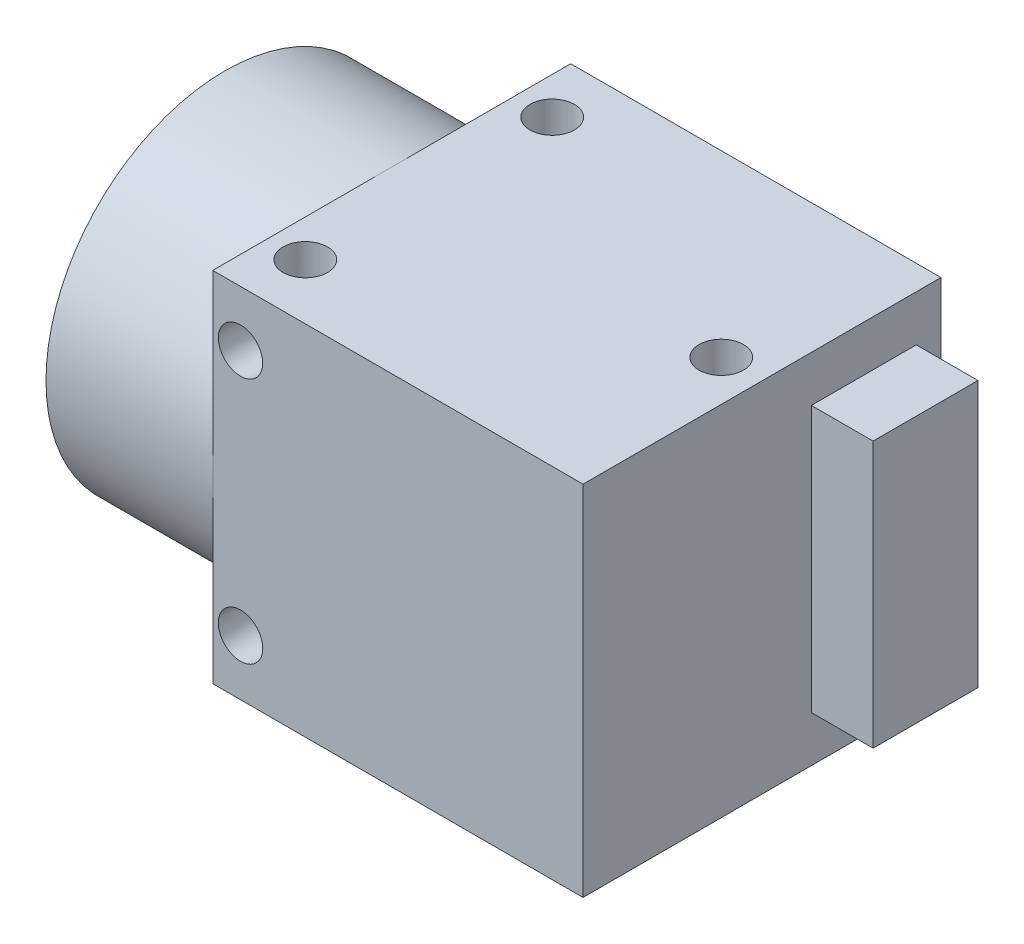
SolidWorks part; units mm, degrees
ref_plane "Front Plane" through (0, 0, 0) normal (0, 0, 1) x (1, 0, 0)
ref_plane "Top Plane" through (0, 0, 0) normal (0, 1, 0) x (1, 0, 0)
ref_plane "Right Plane" through (0, 0, 0) normal (1, 0, 0) x (0, 0, -1)
sketch "Sketch1" plane through (0, 0, 0) normal (1, 0, 0) x (0, -1, 0)
  line L1 (0, 0) -> (29, 0)
  line L2 (0, 0) -> (0, 29)
  line L3 (0, 29) -> (29, 29)
  line L4 (29, 0) -> (29, 29)
  dimension "D1" = 29
extrude "Boss-Extrude1" add sketch "Sketch1" along normal blind 48.51 contours L3 L4 L1 L2
sketch "Sketch2" plane through (0, 0, 0) normal (-1, 0, 0) x (0, 0, 1)
  line L0 (-29, 0) -> (0, -29) construction
  line L1 (0, 0) -> (0, -29) construction
  line L2 (0, -29) -> (-29, -29) construction
  line L3 (0, 0) -> (-29, 0) construction
  line L4 (-29, 0) -> (-29, -29) construction
  line L5 (0, 0) -> (0, -29)
  line L6 (0, -29) -> (-29, -29)
  line L7 (-29, 0) -> (-29, -29)
  line L8 (0, 0) -> (-29, 0)
  circle A0 centre (-14.5, -14.5) radius 14.5
  line M3 (0, 0) -> (-29, 0)
  line M4 (-29, 0) -> (-29, -29)
  line M5 (-29, -29) -> (0, -29)
  line M6 (0, -29) -> (0, 0)
extrude "Cut-Extrude1" cut sketch "Sketch2" against normal blind 13.51 contours L8 L0 A0 | L0 A0 M4 | A0 L7 M5 | L0 A0 L6 | A0 L0 M6 | A0 L5 M3
hole_wizard "M3 Clearance Hole3" positions "Sketch4" profile "Sketch5" hole size "M3" standard "ANSI Metric"
sketch "Sketch4" plane through (0, 0, 0) normal (0, 0, -1) x (1, 0, 0)
  line L0 (15.76, 24.5) -> (15.76, 29) construction
  line L3 (15.76, 4.5) -> (15.76, 0) construction
  line L4 (48.51, 0) -> (13.51, 0) construction
  line L6 (13.51, 14.5) -> (13.51, 0) construction
  line L7 (48.51, 29) -> (13.51, 29) construction
  point P0 (15.76, 24.5)
  point P2 (15.76, 4.5)
  dimension "D1" = 20
  dimension "D2" = 2.25
sketch "Sketch5" plane through (15.76, -24.5, 0) normal (1, 0, 0) x (0, -1, 0)
  line L0 (0, 0) -> (0, 4.0815)
  line L1 (0, 4.0815) -> (1.8, 3)
  line L2 (1.8, 3) -> (1.8, 0)
  line L5 (1.8, 0) -> (0, 0)
  line L10 (0, 4.0815) -> (-1.8, 3) construction
  line L11 (0, -6.35) -> (0, 107.95) construction
  dimension "Hole Dia." = 3.6
  dimension "Hole Depth" = 3
  dimension "Drill Angle" = 118
sketch "Sketch6" plane through (48.51, 0, 0) normal (1, 0, 0) x (0, 0, -1)
  line L0 (27, -3.725) -> (27, 0) construction
  line L1 (18.5, -25.275) -> (18.5, -3.725)
  line L2 (18.5, -25.275) -> (27, -25.275)
  line L3 (27, -25.275) -> (27, -3.725)
  line L4 (18.5, -3.725) -> (27, -3.725)
  line L5 (27, -25.275) -> (27, -29) construction
  line L10 (29, 0) -> (0, 0)
  line L11 (0, 0) -> (0, -29)
  line L12 (0, -29) -> (29, -29)
  line L13 (29, -29) -> (29, 0)
  line L14 (29, 0) -> (0, 0)
  line L15 (0, 0) -> (0, -29)
  line L16 (0, -29) -> (29, -29)
  line L17 (29, -29) -> (29, 0)
  line M11 (29, 0) -> (0, 0)
  line M12 (0, 0) -> (0, -29)
  line M13 (0, -29) -> (29, -29)
  line M14 (29, -29) -> (29, 0)
  dimension "D1" = 21.55
  dimension "D2" = 8.5
  dimension "D4" = 2
  dimension "D3" = 0
extrude "Cut-Extrude2" cut sketch "Sketch6" against normal blind 5 contours L1 L4 L3 L2 M14 M11 M12 M13 | L14 L15 L16 L17
hole_wizard "M3 Clearance Hole2" positions "Sketch8" profile "Sketch9" hole size "M3" standard "ANSI Metric"
sketch "Sketch8" plane through (0, 0, 0) normal (0, 1, 0) x (1, 0, 0)
  line L0 (13.51, 0) -> (13.51, 14.5) construction
  line L1 (16.51, 24.5) -> (16.51, 29) construction
  line L2 (43.51, 29) -> (13.51, 29) construction
  line L4 (16.51, 4.5) -> (16.51, 0) construction
  line L5 (43.51, 0) -> (13.51, 0) construction
  line L7 (16.51, 24.5) -> (16.51, 4.5) construction
  point P0 (16.51, 24.5)
  point P2 (16.51, 4.5)
  point P4 (40.21, 14.5)
  point P28 (16.51, 14.5)
  dimension "D1" = 3
  dimension "D2" = 23.7
  dimension "D3" = 20
sketch "Sketch9" plane through (16.51, 0, -24.5) normal (1, 0, 0) x (0, 0, 1)
  line L0 (0, 0) -> (0, 4.0815)
  line L1 (0, 4.0815) -> (1.8, 3)
  line L2 (1.8, 3) -> (1.8, 0)
  line L5 (1.8, 0) -> (0, 0)
  line L10 (0, 4.0815) -> (-1.8, 3) construction
  line L11 (0, -6.35) -> (0, 107.95) construction
  dimension "Hole Dia." = 3.6
  dimension "Hole Depth" = 3
  dimension "Drill Angle" = 118
